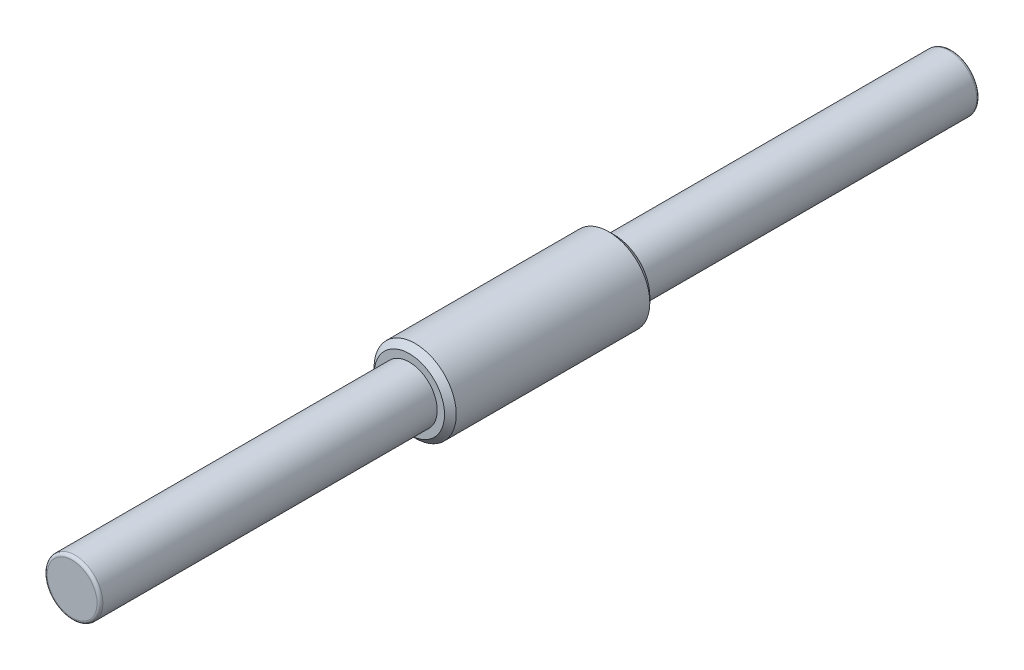
SolidWorks part; units mm, degrees
ref_plane "Front Plane" through (0, 0, 0) normal (0, 0, 1) x (1, 0, 0)
ref_plane "Top Plane" through (0, 0, 0) normal (0, 1, 0) x (1, 0, 0)
ref_plane "Right Plane" through (0, 0, 0) normal (1, 0, 0) x (0, 0, -1)
sketch "Sketch1" plane through (0, 0, 0) normal (0, 0, 1) x (1, 0, 0)
  circle A0 centre (0, 0) radius 0.475
  dimension "D1" = 0.95
extrude "Boss-Extrude1" add sketch "Sketch1" along normal mid plane 15
sketch "Sketch2" plane through (0, 0, 7.5) normal (0, 0, 1) x (1, 0, 0)
  circle A0 centre (0, 0) radius 0.7
  dimension "D1" = 1.4
extrude "Boss-Extrude2" add sketch "Sketch2" against normal blind 3.5 from offset 5.75 separate body offset against normal yes
chamfer "Chamfer1" distance 0.1 angle 45 2 edges at (0.7, 0, -1.75) (0.7, 0, 1.75)
fillet "Fillet1" radius 0.05 2 edges at (0.475, 0, 7.5) (0.475, 0, -7.5)
